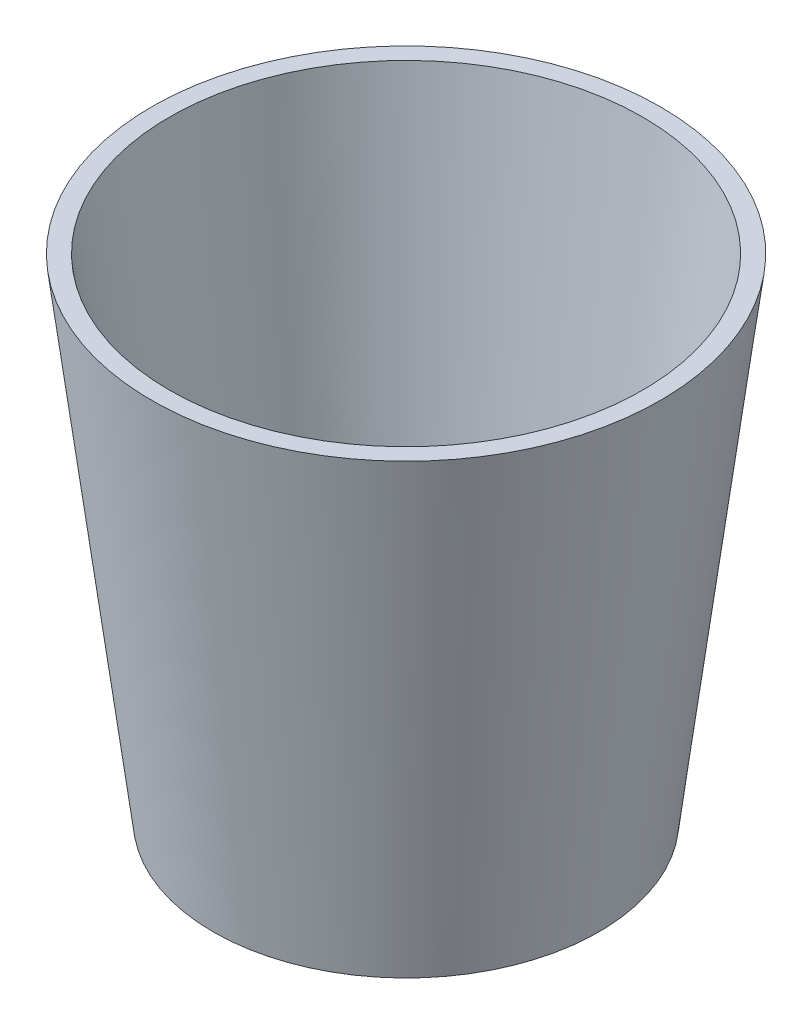
SolidWorks part; units mm, degrees
ref_plane "Front Plane" through (0, 0, 0) normal (0, 0, 1) x (1, 0, 0)
ref_plane "Top Plane" through (0, 0, 0) normal (0, 1, 0) x (1, 0, 0)
ref_plane "Right Plane" through (0, 0, 0) normal (1, 0, 0) x (0, 0, -1)
sketch "Sketch1" plane through (0, 0, 0) normal (1, 0, 0) x (0, 0, -1)
  line L0 (0, 80) -> (-40, 80) construction
  line L1 (0, 0) -> (-30, 0)
  line L2 (-40, 80) -> (-30, 0)
  line L3 (-40, 80) -> (-43, 80)
  line L4 (0, -3) -> (-32.625, -3)
  line L5 (-43, 80) -> (-32.625, -3)
  line L6 (0, 0) -> (0, 80) construction
  line L7 (0, 0) -> (0, -3)
  dimension "D2" = 3
revolve "Revolve1" add sketch "Sketch1" angle 360 about L6
